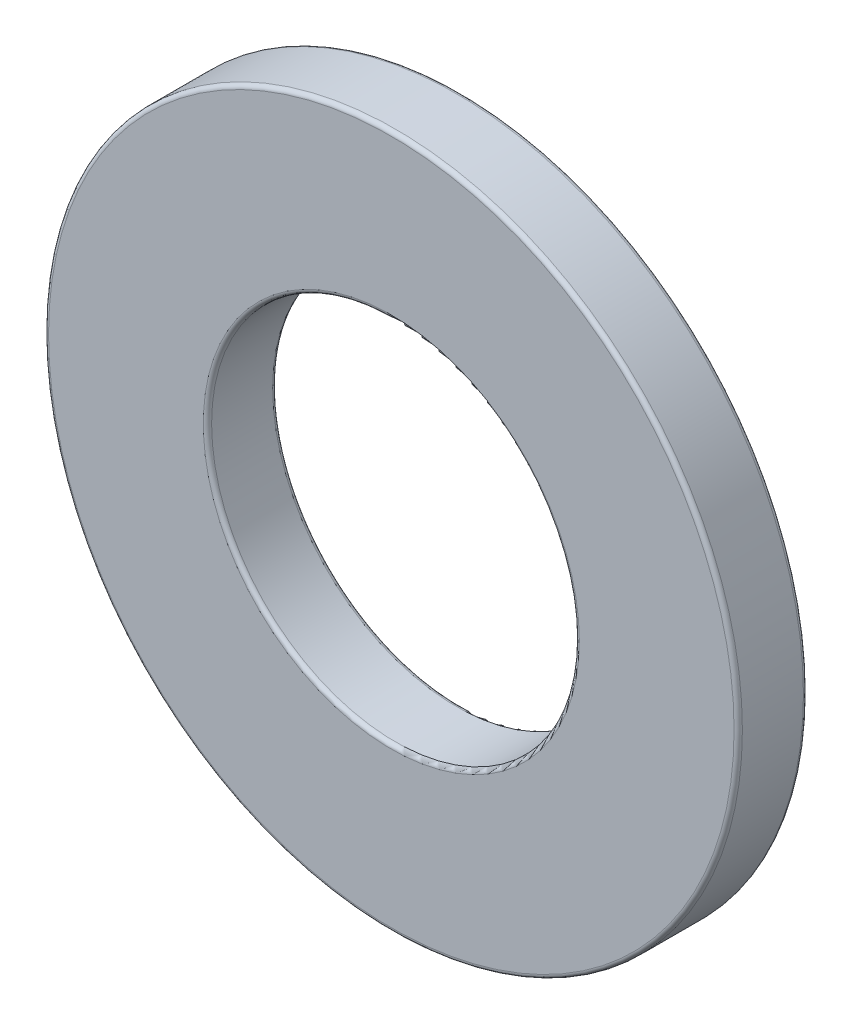
SolidWorks part; units mm, degrees
material "AISI 304"
ref_plane "Front Plane" through (0, 0, 0) normal (0, 0, 1) x (1, 0, 0)
ref_plane "Top Plane" through (0, 0, 0) normal (0, 1, 0) x (1, 0, 0)
ref_plane "Right Plane" through (0, 0, 0) normal (1, 0, 0) x (0, 0, -1)
sketch "Sketch1" plane through (0, 0, 0) normal (0, 0, 1) x (1, 0, 0)
  line L0 (0, 0) -> (2.65, 0) construction
  line L1 (0, -0.165) -> (0, 0.165) construction
  circle A0 centre (0, 0) radius 5
  circle A1 centre (0, 0) radius 2.65
  dimension "D1" = 90
  dimension "OD" = 10
  dimension "ID" = 5.3
sketch "Sketch2" plane through (0, 0, 0) normal (1, 0, 0) x (0, 0, -1)
  line L0 (-0.5, 5) -> (0.5, 5) construction
  point P5 (0, 5)
  dimension "Thickness" = 1
sketch "Sketch3" plane through (0, 0, 0) normal (0, 0, 1) x (1, 0, 0)
  circle A0 centre (0, 0) radius 2.65 construction
  circle A1 centre (0, 0) radius 5 construction
  circle A2 centre (0, 0) radius 2.65
  circle A3 centre (0, 0) radius 5
extrude "Boss-Extrude1" add sketch "Sketch3" against normal up to vertex (0.5 mm away) from vertex at 0.5 starting at point (0, 5, 0.5)
fillet "Fillet1" radius 0.06 4 edges at (5, 0, 0.5) (2.65, 0, 0.5) (5, 0, -0.5) (2.65, 0, -0.5)
